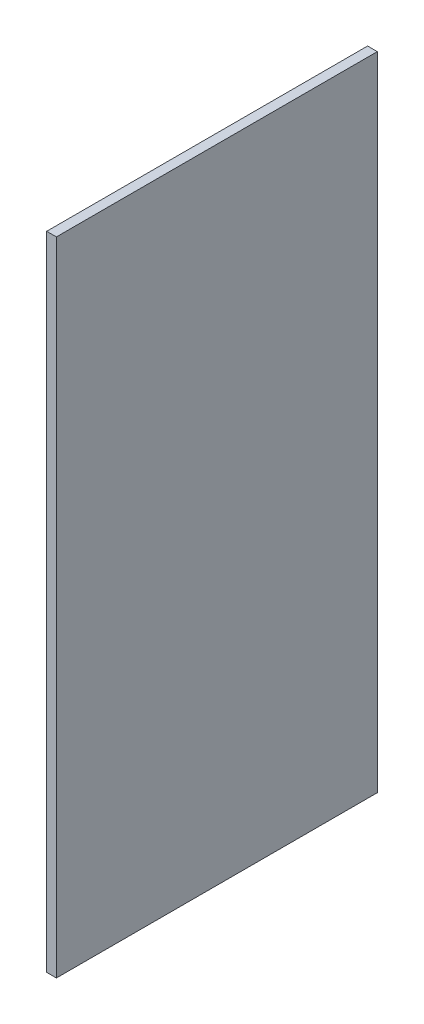
SolidWorks part; units mm, degrees
ref_plane "정면" through (0, 0, 0) normal (0, 0, 1) x (1, 0, 0)
ref_plane "윗면" through (0, 0, 0) normal (0, 1, 0) x (1, 0, 0)
ref_plane "우측면" through (0, 0, 0) normal (1, 0, 0) x (0, 0, -1)
sketch "스케치1" plane through (0, 0, 0) normal (1, 0, 0) x (0, 0, -1)
  line L1 (0, 0) -> (165, 0)
  line L2 (0, 0) -> (0, 330)
  line L3 (0, 330) -> (165, 330)
  line L4 (165, 0) -> (165, 330)
  dimension "D1" = 165
  dimension "D2" = 330
extrude "보스-돌출1" add sketch "스케치1" along normal blind 5
